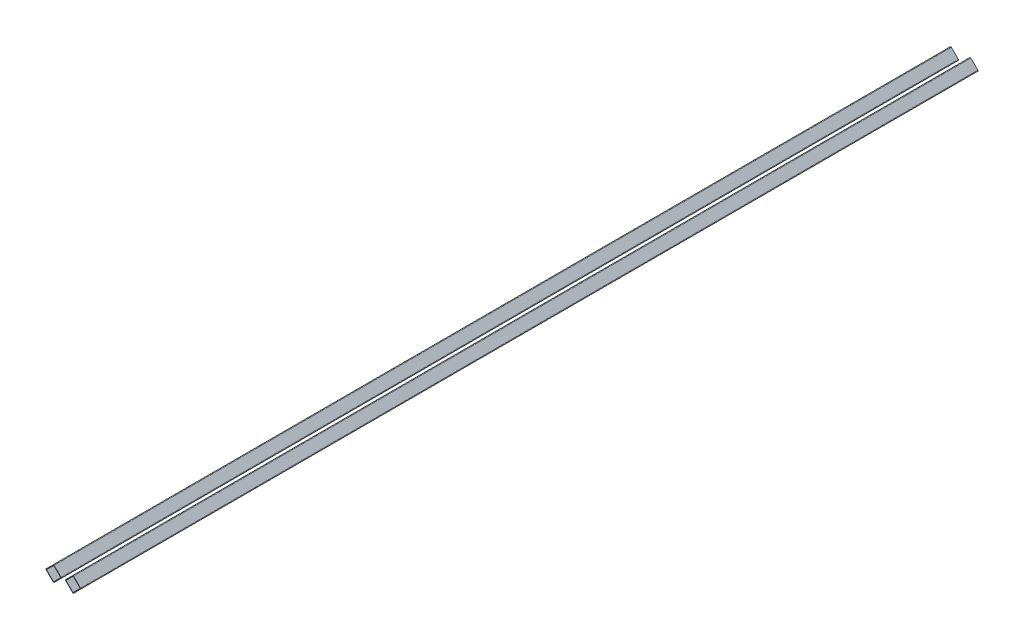
SolidWorks part; units mm, degrees
ref_plane "Front" through (0, 0, 0) normal (0, 0, 1) x (1, 0, 0)
ref_plane "Top" through (0, 0, 0) normal (0, 1, 0) x (1, 0, 0)
ref_plane "Right" through (0, 0, 0) normal (1, 0, 0) x (0, 0, -1)
sketch "inch square tube" plane through (0, 0, 0) normal (0, 0, 1) x (1, 0, 0)
  line L0 (0, 0) -> (-13.4704, -13.4704) construction
  line L1 (25.2437, -1.6971) -> (1.6971, -25.2437)
  line L2 (25.2437, 1.6971) -> (1.6971, 25.2437)
  line L3 (-1.6971, 25.2437) -> (-25.2437, 1.6971)
  line L4 (-1.6971, -25.2437) -> (-25.2437, -1.6971)
  line L5 (0, 0) -> (13.4704, -13.4704) construction
  line L6 (-66.1098, -1.2756) -> (-79.5802, -14.746) construction
  line L7 (-24.1123, 0.5657) -> (-0.5657, 24.1123)
  line L8 (-24.1123, -0.5657) -> (-0.5657, -24.1123)
  line L9 (0.5657, -24.1123) -> (24.1123, -0.5657)
  line L10 (0.5657, 24.1123) -> (24.1123, 0.5657)
  line L11 (-40.8661, -2.9726) -> (-64.4127, -26.5193)
  line L12 (-40.8661, 0.4215) -> (-64.4127, 23.9681)
  line L13 (-67.8068, 23.9681) -> (-91.3535, 0.4215)
  line L14 (-67.8068, -26.5193) -> (-91.3535, -2.9726)
  line L15 (-66.1098, -1.2756) -> (-52.6394, -14.746) construction
  line L16 (-90.2221, -0.7099) -> (-66.6755, 22.8367)
  line L17 (-90.2221, -1.8413) -> (-66.6755, -25.3879)
  line L18 (-65.5441, -25.3879) -> (-41.9974, -1.8413)
  line L19 (-65.5441, 22.8367) -> (-41.9974, -0.7099)
  circle A0 centre (0, 0) radius 14.1224 construction
  arc A1 (1.6971, -25.2437) -> (-1.6971, -25.2437) centre (0, -23.5467) cw
  arc A2 (25.2437, -1.6971) -> (25.2437, 1.6971) centre (23.5467, 0) ccw
  arc A3 (1.6971, 25.2437) -> (-1.6971, 25.2437) centre (0, 23.5467) ccw
  arc A4 (-25.2437, 1.6971) -> (-25.2437, -1.6971) centre (-23.5467, 0) ccw
  arc A5 (-0.5657, 24.1123) -> (0.5657, 24.1123) centre (0, 23.5467) cw
  arc A6 (24.1123, -0.5657) -> (24.1123, 0.5657) centre (23.5467, 0) ccw
  arc A7 (-0.5657, -24.1123) -> (0.5657, -24.1123) centre (0, -23.5467) ccw
  arc A8 (-24.1123, 0.5657) -> (-24.1123, -0.5657) centre (-23.5467, 0) ccw
  circle A9 centre (-66.1098, -1.2756) radius 14.1224 construction
  arc A10 (-64.4127, -26.5193) -> (-67.8068, -26.5193) centre (-66.1098, -24.8222) cw
  arc A11 (-40.8661, -2.9726) -> (-40.8661, 0.4215) centre (-42.5631, -1.2756) ccw
  arc A12 (-64.4127, 23.9681) -> (-67.8068, 23.9681) centre (-66.1098, 22.2711) ccw
  arc A13 (-91.3535, 0.4215) -> (-91.3535, -2.9726) centre (-89.6564, -1.2756) ccw
  arc A14 (-66.6755, 22.8367) -> (-65.5441, 22.8367) centre (-66.1098, 22.2711) cw
  arc A15 (-41.9974, -1.8413) -> (-41.9974, -0.7099) centre (-42.5631, -1.2756) ccw
  arc A16 (-66.6755, -25.3879) -> (-65.5441, -25.3879) centre (-66.1098, -24.8222) ccw
  arc A17 (-90.2221, -0.7099) -> (-90.2221, -1.8413) centre (-89.6564, -1.2756) ccw
  point P0 (0, 0)
  point P1 (-12.339, -12.339)
  point P4 (12.339, -12.339)
  point P7 (-66.1098, -1.2756)
  point P12 (13.4704, 13.4704)
  point P13 (-13.4704, -13.4704)
  point P14 (-13.4704, 13.4704)
  point P35 (0, -26.9408)
  point P36 (13.4704, -13.4704)
  point P37 (-26.9408, 0)
  point P38 (0, 26.9408)
  point P39 (26.9408, 0)
  point P40 (0, 0)
  point P41 (0, 0)
  point P42 (0, 0)
  point P43 (-78.4488, -13.6146)
  point P46 (-53.7708, -13.6146)
  point P53 (-52.6394, 12.1948)
  point P54 (-79.5802, -14.746)
  point P55 (-79.5802, 12.1948)
  point P76 (-66.1098, -28.2164)
  point P77 (-52.6394, -14.746)
  point P78 (-93.0505, -1.2756)
  point P79 (-66.1098, 25.6652)
  point P80 (-39.169, -1.2756)
  point P81 (-66.1098, -1.2756)
  point P82 (-66.1098, -1.2756)
  point P83 (-66.1098, -1.2756)
  dimension "D2" = 14.1224
  dimension "D4" = 2.4
  dimension "D5" = 0.8
  dimension "D6" = 14.1224
  dimension "D8" = 2.4
  dimension "D10" = 0.8
  dimension "D3" = 1.6
  dimension "D1" = 38.1
  dimension "D7" = 1.6
  dimension "D9" = 38.1
extrude "Boss-Extrude1" add sketch "inch square tube" along normal blind 3048
sketch "Sketch1" plane through (0, 0, 3048) normal (0, 0, 1) x (1, 0, 0)
  line L0 (0, 0) -> (0, 24.3467) construction
  line L1 (0, 0) -> (24.3467, 0) construction
  line L2 (0, 0) -> (-24.3467, 0) construction
  line L3 (0, 0) -> (0, -24.3467) construction
  arc A0 (0.5657, 24.1123) -> (-0.5657, 24.1123) centre (0, 23.5467) ccw construction
  arc A1 (24.1123, -0.5657) -> (24.1123, 0.5657) centre (23.5467, 0) ccw construction
  arc A2 (-24.1123, 0.5657) -> (-24.1123, -0.5657) centre (-23.5467, 0) ccw construction
  arc A3 (-0.5657, -24.1123) -> (0.5657, -24.1123) centre (0, -23.5467) ccw construction
  point P0 (0, 0)
equation "\"D4@inch square tube\" = \"D3@inch square tube\" * 1.5"
equation "\"D5@inch square tube\" = \"D4@inch square tube\" - \"D3@inch square tube\""
equation "\"10feet\"=0.6"
